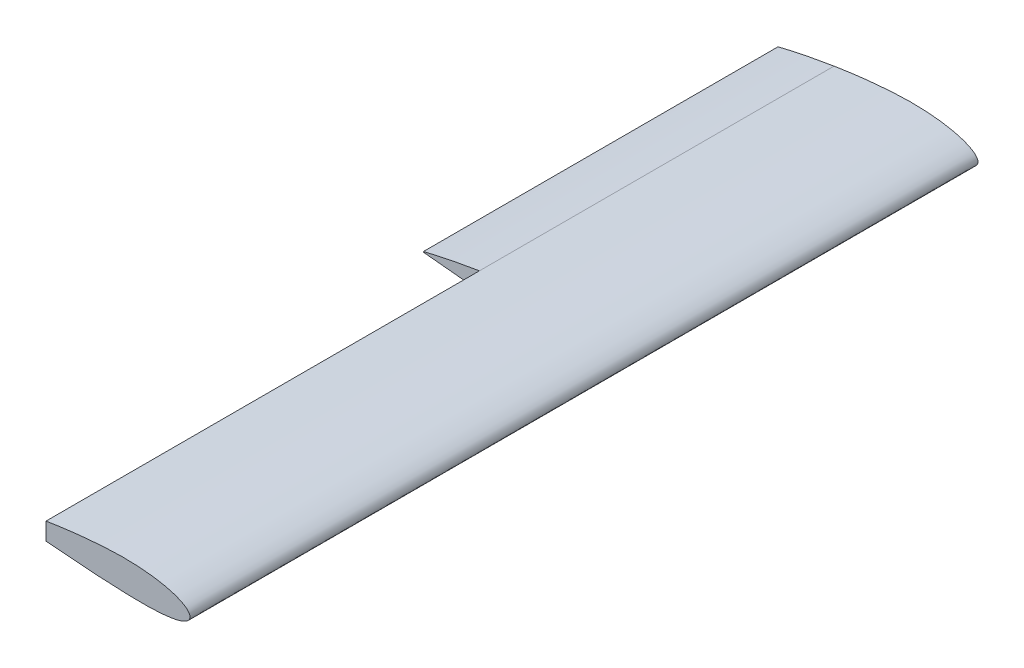
SolidWorks part; units mm, degrees
ref_plane "Front Plane" through (0, 0, 0) normal (0, 0, 1) x (1, 0, 0)
ref_plane "Top Plane" through (0, 0, 0) normal (0, 1, 0) x (1, 0, 0)
ref_plane "Right Plane" through (0, 0, 0) normal (1, 0, 0) x (0, 0, -1)
sketch "Sketch1" plane through (0, 0, 0) normal (0, 0, 1) x (1, 0, 0)
  line L0 (-204.6067, 16.4337) -> (-204.6067, -8.1987)
  spline S0 degree 3 poles (-204.6067, 16.4337) (-202.0364, 16.8435) (-195.9768, 17.8096) (-186.3199, 19.2196) (-175.5722, 20.6819) (-164.6073, 22.0386) (-153.494, 23.2716) (-142.3015, 24.3576) (-131.0997, 25.2761) (-119.9435, 26.0067) (-108.8824, 26.5372) (-97.9847, 26.7846) (-87.3392, 26.7465) (-77.0378, 26.4169) (-67.1496, 25.7985) (-57.7411, 24.8989) (-48.875, 23.7311) (-40.6098, 22.3135) (-32.999, 20.6688) (-26.0908, 18.8238) (-19.9273, 16.8078) (-14.5439, 14.6516) (-9.9686, 12.3852) (-6.2214, 10.0358) (-3.3137, 7.6219) (-1.2528, 5.1467) (-0.0675, 2.5867) (0.1546, -0.0155) (-0.5776, -2.5202) (-2.2311, -4.7957) (-4.7051, -6.8272) (-7.9698, -8.6527) (-12.012, -10.2839) (-16.8128, -11.7212) (-22.346, -12.9608) (-28.5794, -13.9994) (-35.4759, -14.8356) (-42.995, -15.4709) (-51.093, -15.9105) (-59.7234, -16.1628) (-68.8374, -16.2403) (-78.3839, -16.1585) (-88.3098, -15.9358) (-98.5596, -15.5937) (-109.0967, -15.1513) (-119.8773, -14.6385) (-130.8353, -14.0093) (-141.8845, -13.2901) (-152.9424, -12.4996) (-163.9423, -11.6567) (-174.817, -10.7785) (-185.4999, -9.8796) (-195.4089, -9.0211) (-201.7486, -8.4543) (-204.6067, -8.1987) knots 0 0 0 0 0.018424 0.043434 0.06908 0.095203 0.12164 0.148227 0.1748 0.201195 0.227364 0.253182 0.278347 0.30271 0.326128 0.348467 0.3696 0.389416 0.407811 0.424699 0.440008 0.453688 0.465715 0.476104 0.484928 0.49236 0.49873 0.504587 0.510443 0.516804 0.524199 0.532941 0.543186 0.554996 0.568376 0.583299 0.599709 0.617539 0.636704 0.657109 0.678651 0.701217 0.724685 0.748928 0.773811 0.799338 0.825326 0.851504 0.877716 0.9038 0.929596 0.954944 0.979688 1 1 1 1
extrude "Boss-Extrude1" add sketch "Sketch1" along normal blind 1120
sketch "Sketch2" plane through (0, 0, 0) normal (0, 0, 1) x (1, 0, 0)
  line L0 (-204.6067, 16.4337) -> (-204.6067, -8.1987)
  line L1 (-284.176, 0.4539) -> (-284.176, -0.4466)
  spline S0 degree 3 poles (-204.6067, 16.4337) (-205.4155, 16.3071) (-209.473, 15.6715) (-216.6128, 14.4575) (-225.8556, 12.8273) (-234.5737, 11.204) (-242.7164, 9.6201) (-250.2346, 8.0967) (-257.084, 6.6573) (-263.2241, 5.3239) (-268.6191, 4.1181) (-273.2376, 3.0598) (-277.0529, 2.1669) (-280.0432, 1.4552) (-282.1913, 0.9372) (-283.4751, 0.6251) (-284.0416, 0.4867) (-284.176, 0.4539) knots 0 0 0 0 0.030252 0.151774 0.267626 0.37709 0.479485 0.574175 0.66057 0.73813 0.806369 0.864859 0.913229 0.951173 0.978451 0.994887 1 1 1 1
  spline S1 degree 3 poles (-204.6067, -8.1987) (-205.1233, -8.1528) (-208.8868, -7.8183) (-215.7471, -7.1903) (-225.0196, -6.3324) (-233.7877, -5.5056) (-241.996, -4.7193) (-249.5923, -3.9801) (-256.5279, -3.2948) (-262.7581, -2.6701) (-268.2426, -2.1118) (-272.9458, -1.6282) (-276.8367, -1.2191) (-279.8905, -0.906) (-282.085, -0.6533) (-283.41, -0.5467) (-284.0076, -0.446) (-284.1661, -0.4466) (-284.176, -0.4466) knots 0 0 0 0 0.019463 0.141781 0.258505 0.3689 0.472262 0.567931 0.655294 0.733785 0.802892 0.862162 0.911205 0.949694 0.977373 0.994054 0.999628 1 1 1 1
extrude "Boss-Extrude2" add sketch "Sketch2" along normal blind 504
sketch "Sketch3" plane through (0, 0, 0) normal (0, 0, 1) x (1, 0, 0)
  circle A0 centre (-85.253, 5.328) radius 12.7
extrude "Cut-Extrude1" cut sketch "Sketch3" along normal blind 801
ref_plane "Plane1" through (0, 0, 330.7) normal (0, 0, 1) x (1, 0, 0)
sketch "Sketch4" plane through (0, 0, 330.7) normal (0, 0, 1) x (1, 0, 0)
  line L0 (-101.253, -16.991) -> (-69.253, -16.991)
  line L1 (-69.253, -16.991) -> (-69.253, 21.028)
  line L2 (-69.253, 21.028) -> (-101.253, 21.028)
  line L3 (-101.253, 21.028) -> (-101.253, -16.991)
extrude "Cut-Extrude2" cut sketch "Sketch4" along normal blind 46
ref_plane "Plane2" through (0, 0, 330.7) normal (0, 0, 1) x (1, 0, 0)
sketch "Sketch5" plane through (0, 0, 330.7) normal (0, 0, 1) x (1, 0, 0)
  line L0 (-257.3408, -8.16) -> (-197.3408, -8.16)
  line L1 (-197.3408, -8.16) -> (-197.3408, 3.84)
  line L2 (-197.3408, 3.84) -> (-257.3408, 3.84)
  line L3 (-257.3408, 3.84) -> (-257.3408, -8.16)
extrude "Cut-Extrude3" cut sketch "Sketch5" along normal blind 46
ref_plane "Plane3" through (0, 0, 534.5) normal (0, 0, 1) x (1, 0, 0)
sketch "Sketch6" plane through (0, 0, 534.5) normal (0, 0, 1) x (1, 0, 0)
  line L0 (-183.297, -15.264) -> (-129.297, -15.264)
  line L1 (-129.297, -15.264) -> (-129.297, 13.836)
  line L2 (-129.297, 13.836) -> (-183.297, 13.836)
  line L3 (-183.297, 13.836) -> (-183.297, -15.264)
extrude "Cut-Extrude4" cut sketch "Sketch6" along normal blind 64
ref_plane "Plane4" through (0, 0, -0.5) normal (0, 0, 1) x (1, 0, 0)
sketch "Sketch7" plane through (0, 0, -0.5) normal (0, 0, 1) x (1, 0, 0)
  line L0 (-209.123, 0.863) -> (-188.723, 0.863)
  line L1 (-188.723, 0.863) -> (-188.723, 7.663)
  line L2 (-188.723, 7.663) -> (-209.123, 7.663)
  line L3 (-209.123, 7.663) -> (-209.123, 0.863)
extrude "Cut-Extrude5" cut sketch "Sketch7" along normal blind 26
